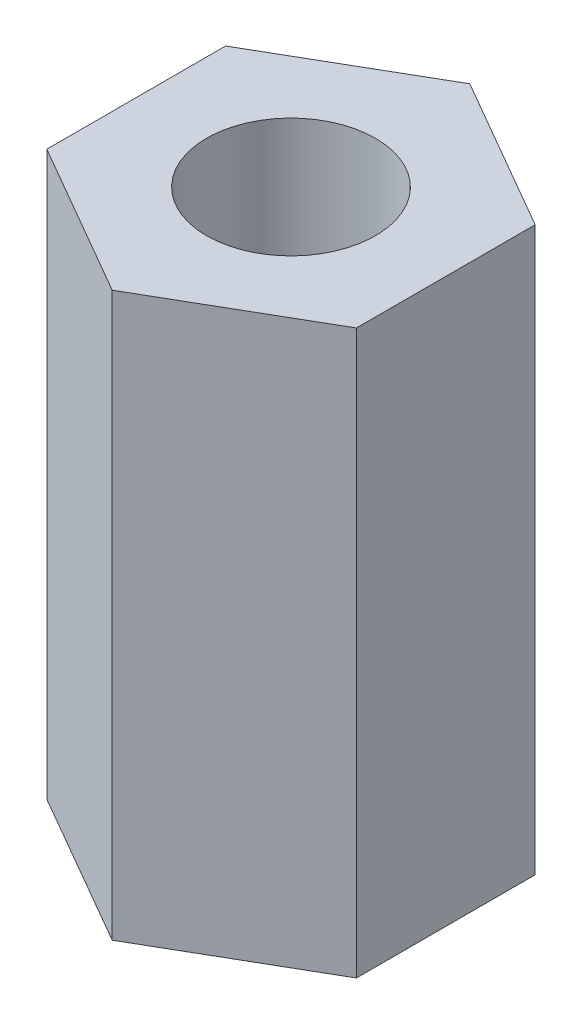
SolidWorks part; units mm, degrees
ref_plane "前视基准面" through (0, 0, 0) normal (0, 0, 1) x (1, 0, 0)
ref_plane "上视基准面" through (0, 0, 0) normal (0, 1, 0) x (1, 0, 0)
ref_plane "右视基准面" through (0, 0, 0) normal (1, 0, 0) x (0, 0, -1)
other "Configuration Table"
sketch "草图1" plane through (0, 0, 0) normal (0, 1, 0) x (1, 0, 0)
  line L1 (0, 3.1754) -> (-2.75, 1.5877)
  line L2 (-2.75, 1.5877) -> (-2.75, -1.5877)
  line L3 (-2.75, -1.5877) -> (0, -3.1754)
  line L4 (0, -3.1754) -> (2.75, -1.5877)
  line L5 (2.75, -1.5877) -> (2.75, 1.5877)
  line L6 (2.75, 1.5877) -> (0, 3.1754)
  circle A0 centre (0, 0) radius 2.75 construction
  circle A1 centre (0, 0) radius 1.5
  dimension "D2" = 3
  dimension "D1" = 5.5
extrude "凸台-拉伸1" add sketch "草图1" along normal blind 10
